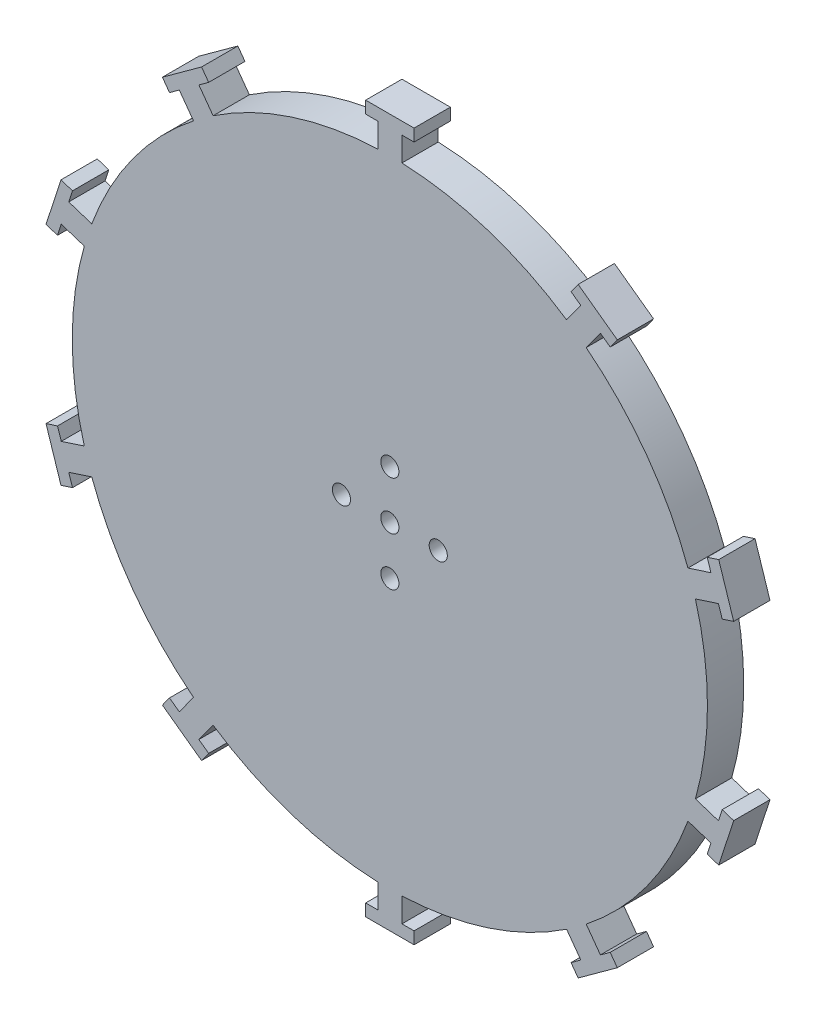
SolidWorks part; units mm, degrees
ref_plane "Front Plane" through (0, 0, 0) normal (0, 0, 1) x (1, 0, 0)
ref_plane "Top Plane" through (0, 0, 0) normal (0, 1, 0) x (1, 0, 0)
ref_plane "Right Plane" through (0, 0, 0) normal (1, 0, 0) x (0, 0, -1)
sketch "Sketch1" plane through (0, 0, 0) normal (0, 0, 1) x (1, 0, 0)
  circle A0 centre (0, 0) radius 52.5
  dimension "D1" = 105
extrude "Boss-Extrude1" add sketch "Sketch1" along normal blind 2
sketch "Sketch6" plane through (0, 0, 0) normal (0, 0, 1) x (1, 0, 0)
  line L0 (-2, 52.4619) -> (-2, 56.4619)
  line L1 (0, 37.6165) -> (0, 55.5597) construction
  line L2 (2, 52.4619) -> (2, 56.4619)
  line L3 (-2, 56.4619) -> (-4, 56.4619)
  line L4 (-4, 56.4619) -> (-4, 58.4619)
  line L5 (-4, 58.4619) -> (4, 58.4619)
  line L6 (4, 58.4619) -> (4, 56.4619)
  line L7 (4, 56.4619) -> (2, 56.4619)
  circle A0 centre (0, 0) radius 52.5 construction
  circle A2 centre (0, 0) radius 52.5
  arc A3 (-2, 52.4619) -> (2, 52.4619) centre (0, 0) ccw
  dimension "D1" = 4
  dimension "D2" = 4
  dimension "D3" = 2
  dimension "D4" = 2
  dimension "D5" = 0
extrude "Boss-Extrude2" add sketch "Sketch6" along normal blind 6
pattern_circular "CirPattern1" count 10 over 360 about axis through (0, 0, 0) along (0, 0, 1) of "Boss-Extrude2"
sketch "Sketch4" plane through (0, 0, 6) normal (0, 0, 1) x (1, 0, 0)
  line L0 (0, -3.3) -> (0, 3.3) construction
  circle A0 centre (0, 8) radius 1.5
  circle A1 centre (0, 0) radius 1.5
  circle A4 centre (8, 0) radius 1.5
  circle A5 centre (0, -8) radius 1.5
  circle A6 centre (-8, 0) radius 1.5
  point P15 (0, 0)
  dimension "D1" = 3
  dimension "D2" = 8
  dimension "D4" = 3
  dimension "D3" = 4
extrude "Cut-Extrude2" cut sketch "Sketch4" against normal mid plane 20
equation "\"diameter\"=80"
equation "\"D1\" = \"diameter\" / 2"
